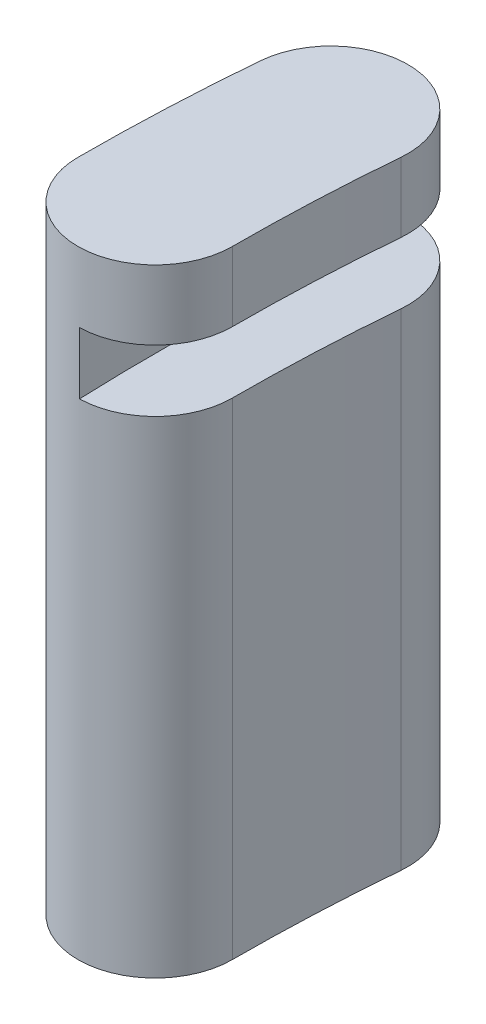
SolidWorks part; units mm, degrees
ref_plane "Front Plane" through (0, 0, 0) normal (0, 0, 1) x (1, 0, 0)
ref_plane "Top Plane" through (0, 0, 0) normal (0, 1, 0) x (1, 0, 0)
ref_plane "Right Plane" through (0, 0, 0) normal (1, 0, 0) x (0, 0, -1)
sketch "Sketch1" plane through (0, 0, 0) normal (0, 1, 0) x (1, 0, 0)
  arc A1 (-124.5243, 10.8945) -> (-125, 0) centre (0, 0) ccw construction
  arc A2 (-124.5243, 10.8945) -> (-125, 0) centre (0, 0) ccw construction
  arc A3 (-129.5053, 11.3302) -> (-130, 0) centre (0, 0) ccw
  arc A4 (-119.5434, 10.4587) -> (-120, 0) centre (0, 0) ccw
  arc A5 (-119.5434, 10.4587) -> (-129.5053, 11.3302) centre (-124.5243, 10.8945) ccw
  arc A6 (-130, 0) -> (-120, 0) centre (-125, 0) ccw
  point P1 (-124.7962, 7.1357)
  point P6 (-124.881, 5.4524)
  point P11 (0, 0)
  point P12 (-124.8499, 5.0224)
  point P13 (0, 0)
  point P14 (-124.9085, -4.7811)
  point P15 (0, 0)
  point P16 (-124.7204, -10.556)
  point P17 (-124.6721, 9.0478)
  point P18 (0, 0)
  point P19 (0, 0)
  point P20 (0, 0)
  point P21 (-124.9893, -1.6318)
  point P22 (-119.7091, 8.3508)
  point P23 (-110.1984, -47.5006)
  point P24 (0, 0)
  point P25 (0, 0)
  point P26 (0, 0)
  point P27 (0, 0)
  dimension "D1" = 125
  dimension "D3" = 10
  dimension "D2" = 5
extrude "Boss-Extrude1" add sketch "Sketch1" along normal blind 40
ref_plane "Plane1" through (0, 31.5, 0) normal (0, -1, 0) x (-1, 0, 0)
sketch "Sketch2" plane through (0, 31.5, 0) normal (0, 1, 0) x (1, 0, 0)
  arc A2 (-130, 0) -> (-120, 0) centre (-125, 0) ccw construction
  arc A4 (-124.9, -4.999) -> (-120, 0) centre (-125, 0) ccw
  arc A5 (-119.5434, 10.4587) -> (-120, 0) centre (0, 0) ccw construction
  arc A6 (-119.5434, 10.4587) -> (-120, 0) centre (0, 0) ccw
  arc A8 (-123.989, 15.8657) -> (-119.5434, 10.4587) centre (-124.5243, 10.8945) cw
  arc A9 (-119.5434, 10.4587) -> (-129.5053, 11.3302) centre (-124.5243, 10.8945) ccw construction
  arc A11 (-123.989, 15.8657) -> (-124.9, -4.999) centre (0, 0) ccw
  arc A12 (-124.5243, 10.8945) -> (-125, 0) centre (0, 0) ccw construction
  point P5 (0, 0)
  point P24 (0, 0)
extrude "Cut-Extrude4" cut sketch "Sketch2" along normal blind 4
